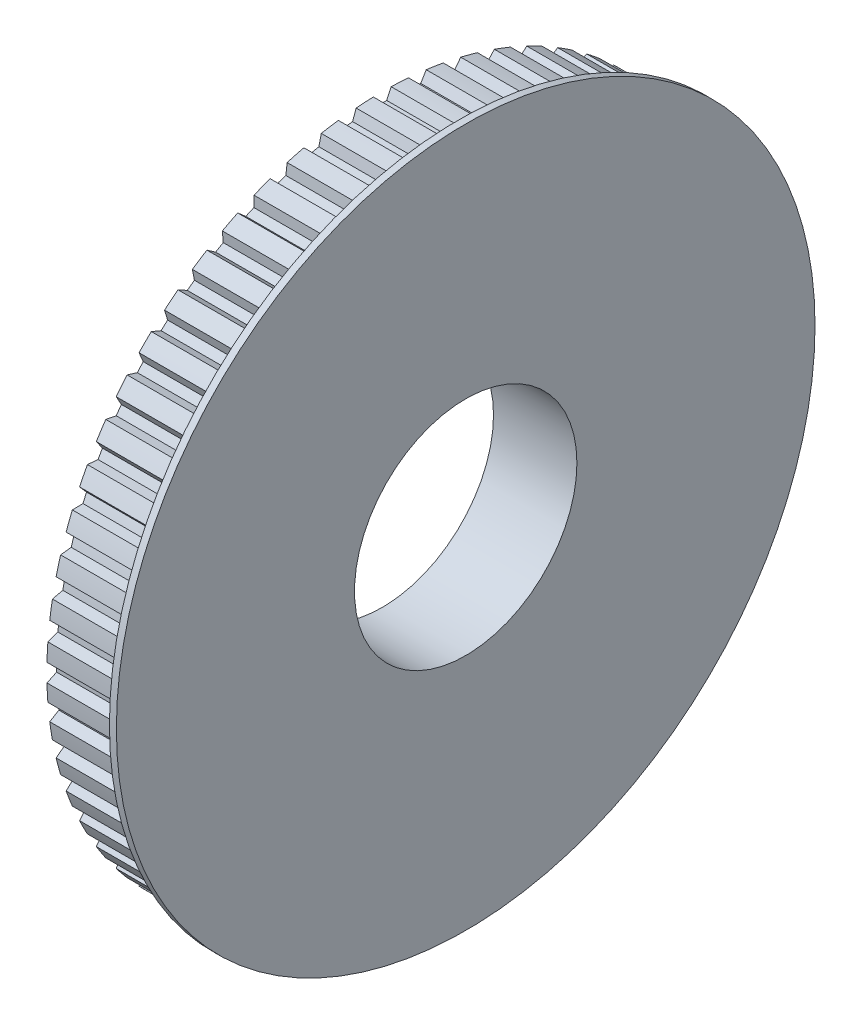
SolidWorks part; units mm, degrees
ref_plane "Front Plane" through (0, 0, 0) normal (0, 0, 1) x (1, 0, 0)
ref_plane "Top Plane" through (0, 0, 0) normal (0, 1, 0) x (1, 0, 0)
ref_plane "Right Plane" through (0, 0, 0) normal (1, 0, 0) x (0, 0, -1)
sketch "Sketch1" plane through (0, 0, 0) normal (1, 0, 0) x (0, 0, -1)
  line L0 (0, 48.255) -> (0, 0) construction
  circle A0 centre (0, 0) radius 48.255
  circle A1 centre (0, 0) radius 16
  point P19 (0, 0)
  dimension "D1" = 96.51
  dimension "D2" = 32
extrude "Boss-Extrude1" add sketch "Sketch1" along normal blind 11
sketch "Sketch2" plane through (0, 0, 0) normal (-1, 0, 0) x (0, 0, 1)
  line L0 (0, 0) -> (0, 48.255) construction
  line L1 (1.2819, 48.238) -> (0.635, 46.8507)
  line L2 (-1.2819, 48.238) -> (-0.635, 46.8507)
  line L3 (6.3171, 47.8397) -> (5.5287, 46.5277)
  line L4 (3.7674, 48.1077) -> (4.2657, 46.6604)
  line L5 (11.2831, 46.9173) -> (10.3619, 45.6949)
  line L6 (8.7754, 47.4504) -> (9.1197, 45.9589)
  line L7 (16.1255, 45.4809) -> (15.0816, 44.3614)
  line L8 (13.6872, 46.2732) -> (13.8738, 44.7539)
  line L9 (20.7912, 43.5462) -> (19.636, 42.542)
  line L10 (18.4491, 44.589) -> (18.4758, 43.0585)
  line L11 (25.2291, 41.1344) -> (23.9753, 40.2564)
  line L12 (23.0088, 42.4162) -> (22.8754, 40.8914)
  line L13 (29.3906, 38.2719) -> (28.0519, 37.5298)
  line L14 (27.3165, 39.7788) -> (27.0244, 38.2762)
  line L15 (33.2301, 34.9901) -> (31.8211, 34.392)
  line L16 (31.3249, 36.7055) -> (30.8774, 35.2417)
  line L17 (36.7055, 31.3249) -> (35.2417, 30.8774)
  line L18 (34.9901, 33.2301) -> (34.392, 31.8211)
  line L19 (39.7788, 27.3165) -> (38.2762, 27.0244)
  line L20 (38.2719, 29.3906) -> (37.5298, 28.0519)
  line L21 (42.4162, 23.0088) -> (40.8914, 22.8754)
  line L22 (41.1344, 25.2291) -> (40.2564, 23.9753)
  line L23 (44.589, 18.4491) -> (43.0585, 18.4758)
  line L24 (43.5462, 20.7912) -> (42.542, 19.636)
  line L25 (46.2732, 13.6872) -> (44.7539, 13.8738)
  line L26 (45.4809, 16.1255) -> (44.3614, 15.0816)
  line L27 (47.4504, 8.7754) -> (45.9589, 9.1197)
  line L28 (46.9173, 11.2831) -> (45.6949, 10.3619)
  line L29 (48.1077, 3.7674) -> (46.6604, 4.2657)
  line L30 (47.8397, 6.3171) -> (46.5277, 5.5287)
  line L31 (48.238, -1.2819) -> (46.8507, -0.635)
  line L32 (48.238, 1.2819) -> (46.8507, 0.635)
  line L33 (47.8397, -6.3171) -> (46.5277, -5.5287)
  line L34 (48.1077, -3.7674) -> (46.6604, -4.2657)
  line L35 (46.9173, -11.2831) -> (45.6949, -10.3619)
  line L36 (47.4504, -8.7754) -> (45.9589, -9.1197)
  line L37 (45.4809, -16.1255) -> (44.3614, -15.0816)
  line L38 (46.2732, -13.6872) -> (44.7539, -13.8738)
  line L39 (43.5462, -20.7912) -> (42.542, -19.636)
  line L40 (44.589, -18.4491) -> (43.0585, -18.4758)
  line L41 (41.1344, -25.2291) -> (40.2564, -23.9753)
  line L42 (42.4162, -23.0088) -> (40.8914, -22.8754)
  line L43 (38.2719, -29.3906) -> (37.5298, -28.0519)
  line L44 (39.7788, -27.3165) -> (38.2762, -27.0244)
  line L45 (34.9901, -33.2301) -> (34.392, -31.8211)
  line L46 (36.7055, -31.3249) -> (35.2417, -30.8774)
  line L47 (31.3249, -36.7055) -> (30.8774, -35.2417)
  line L48 (33.2301, -34.9901) -> (31.8211, -34.392)
  line L49 (27.3165, -39.7788) -> (27.0244, -38.2762)
  line L50 (29.3906, -38.2719) -> (28.0519, -37.5298)
  line L51 (23.0088, -42.4162) -> (22.8754, -40.8914)
  line L52 (25.2291, -41.1344) -> (23.9753, -40.2564)
  line L53 (18.4491, -44.589) -> (18.4758, -43.0585)
  line L54 (20.7912, -43.5462) -> (19.636, -42.542)
  line L55 (13.6872, -46.2732) -> (13.8738, -44.7539)
  line L56 (16.1255, -45.4809) -> (15.0816, -44.3614)
  line L57 (8.7754, -47.4504) -> (9.1197, -45.9589)
  line L58 (11.2831, -46.9173) -> (10.3619, -45.6949)
  line L59 (3.7674, -48.1077) -> (4.2657, -46.6604)
  line L60 (6.3171, -47.8397) -> (5.5287, -46.5277)
  line L61 (-1.2819, -48.238) -> (-0.635, -46.8507)
  line L62 (1.2819, -48.238) -> (0.635, -46.8507)
  line L63 (-6.3171, -47.8397) -> (-5.5287, -46.5277)
  line L64 (-3.7674, -48.1077) -> (-4.2657, -46.6604)
  line L65 (-11.2831, -46.9173) -> (-10.3619, -45.6949)
  line L66 (-8.7754, -47.4504) -> (-9.1197, -45.9589)
  line L67 (-16.1255, -45.4809) -> (-15.0816, -44.3614)
  line L68 (-13.6872, -46.2732) -> (-13.8738, -44.7539)
  line L69 (-20.7912, -43.5462) -> (-19.636, -42.542)
  line L70 (-18.4491, -44.589) -> (-18.4758, -43.0585)
  line L71 (-25.2291, -41.1344) -> (-23.9753, -40.2564)
  line L72 (-23.0088, -42.4162) -> (-22.8754, -40.8914)
  line L73 (-29.3906, -38.2719) -> (-28.0519, -37.5298)
  line L74 (-27.3165, -39.7788) -> (-27.0244, -38.2762)
  line L75 (-33.2301, -34.9901) -> (-31.8211, -34.392)
  line L76 (-31.3249, -36.7055) -> (-30.8774, -35.2417)
  line L77 (-36.7055, -31.3249) -> (-35.2417, -30.8774)
  line L78 (-34.9901, -33.2301) -> (-34.392, -31.8211)
  line L79 (-39.7788, -27.3165) -> (-38.2762, -27.0244)
  line L80 (-38.2719, -29.3906) -> (-37.5298, -28.0519)
  line L81 (-42.4162, -23.0088) -> (-40.8914, -22.8754)
  line L82 (-41.1344, -25.2291) -> (-40.2564, -23.9753)
  line L83 (-44.589, -18.4491) -> (-43.0585, -18.4758)
  line L84 (-43.5462, -20.7912) -> (-42.542, -19.636)
  line L85 (-46.2732, -13.6872) -> (-44.7539, -13.8738)
  line L86 (-45.4809, -16.1255) -> (-44.3614, -15.0816)
  line L87 (-47.4504, -8.7754) -> (-45.9589, -9.1197)
  line L88 (-46.9173, -11.2831) -> (-45.6949, -10.3619)
  line L89 (-48.1077, -3.7674) -> (-46.6604, -4.2657)
  line L90 (-47.8397, -6.3171) -> (-46.5277, -5.5287)
  line L91 (-48.238, 1.2819) -> (-46.8507, 0.635)
  line L92 (-48.238, -1.2819) -> (-46.8507, -0.635)
  line L93 (-47.8397, 6.3171) -> (-46.5277, 5.5287)
  line L94 (-48.1077, 3.7674) -> (-46.6604, 4.2657)
  line L95 (-46.9173, 11.2831) -> (-45.6949, 10.3619)
  line L96 (-47.4504, 8.7754) -> (-45.9589, 9.1197)
  line L97 (-45.4809, 16.1255) -> (-44.3614, 15.0816)
  line L98 (-46.2732, 13.6872) -> (-44.7539, 13.8738)
  line L99 (-43.5462, 20.7912) -> (-42.542, 19.636)
  line L100 (-44.589, 18.4491) -> (-43.0585, 18.4758)
  line L101 (-41.1344, 25.2291) -> (-40.2564, 23.9753)
  line L102 (-42.4162, 23.0088) -> (-40.8914, 22.8754)
  line L103 (-38.2719, 29.3906) -> (-37.5298, 28.0519)
  line L104 (-39.7788, 27.3165) -> (-38.2762, 27.0244)
  line L105 (-34.9901, 33.2301) -> (-34.392, 31.8211)
  line L106 (-36.7055, 31.3249) -> (-35.2417, 30.8774)
  line L107 (-31.3249, 36.7055) -> (-30.8774, 35.2417)
  line L108 (-33.2301, 34.9901) -> (-31.8211, 34.392)
  line L109 (-27.3165, 39.7788) -> (-27.0244, 38.2762)
  line L110 (-29.3906, 38.2719) -> (-28.0519, 37.5298)
  line L111 (-23.0088, 42.4162) -> (-22.8754, 40.8914)
  line L112 (-25.2291, 41.1344) -> (-23.9753, 40.2564)
  line L113 (-18.4491, 44.589) -> (-18.4758, 43.0585)
  line L114 (-20.7912, 43.5462) -> (-19.636, 42.542)
  line L115 (-13.6872, 46.2732) -> (-13.8738, 44.7539)
  line L116 (-16.1255, 45.4809) -> (-15.0816, 44.3614)
  line L117 (-8.7754, 47.4504) -> (-9.1197, 45.9589)
  line L118 (-11.2831, 46.9173) -> (-10.3619, 45.6949)
  line L119 (-3.7674, 48.1077) -> (-4.2657, 46.6604)
  line L120 (-6.3171, 47.8397) -> (-5.5287, 46.5277)
  circle A0 centre (0, 0) radius 48.255 construction
  arc A1 (1.2819, 48.238) -> (-1.2819, 48.238) centre (0, 0) ccw
  arc A2 (0.635, 46.8507) -> (-0.635, 46.8507) centre (0, 0) ccw
  arc A3 (6.3171, 47.8397) -> (3.7674, 48.1077) centre (0, 0) ccw
  arc A4 (5.5287, 46.5277) -> (4.2657, 46.6604) centre (0, 0) ccw
  arc A5 (11.2831, 46.9173) -> (8.7754, 47.4504) centre (0, 0) ccw
  arc A6 (10.3619, 45.6949) -> (9.1197, 45.9589) centre (0, 0) ccw
  arc A7 (16.1255, 45.4809) -> (13.6872, 46.2732) centre (0, 0) ccw
  arc A8 (15.0816, 44.3614) -> (13.8738, 44.7539) centre (0, 0) ccw
  arc A9 (20.7912, 43.5462) -> (18.4491, 44.589) centre (0, 0) ccw
  arc A10 (19.636, 42.542) -> (18.4758, 43.0585) centre (0, 0) ccw
  arc A11 (25.2291, 41.1344) -> (23.0088, 42.4162) centre (0, 0) ccw
  arc A12 (23.9753, 40.2564) -> (22.8754, 40.8914) centre (0, 0) ccw
  arc A13 (29.3906, 38.2719) -> (27.3165, 39.7788) centre (0, 0) ccw
  arc A14 (28.0519, 37.5298) -> (27.0244, 38.2762) centre (0, 0) ccw
  arc A15 (33.2301, 34.9901) -> (31.3249, 36.7055) centre (0, 0) ccw
  arc A16 (31.8211, 34.392) -> (30.8774, 35.2417) centre (0, 0) ccw
  arc A17 (36.7055, 31.3249) -> (34.9901, 33.2301) centre (0, 0) ccw
  arc A18 (35.2417, 30.8774) -> (34.392, 31.8211) centre (0, 0) ccw
  arc A19 (39.7788, 27.3165) -> (38.2719, 29.3906) centre (0, 0) ccw
  arc A20 (38.2762, 27.0244) -> (37.5298, 28.0519) centre (0, 0) ccw
  arc A21 (42.4162, 23.0088) -> (41.1344, 25.2291) centre (0, 0) ccw
  arc A22 (40.8914, 22.8754) -> (40.2564, 23.9753) centre (0, 0) ccw
  arc A23 (44.589, 18.4491) -> (43.5462, 20.7912) centre (0, 0) ccw
  arc A24 (43.0585, 18.4758) -> (42.542, 19.636) centre (0, 0) ccw
  arc A25 (46.2732, 13.6872) -> (45.4809, 16.1255) centre (0, 0) ccw
  arc A26 (44.7539, 13.8738) -> (44.3614, 15.0816) centre (0, 0) ccw
  arc A27 (47.4504, 8.7754) -> (46.9173, 11.2831) centre (0, 0) ccw
  arc A28 (45.9589, 9.1197) -> (45.6949, 10.3619) centre (0, 0) ccw
  arc A29 (48.1077, 3.7674) -> (47.8397, 6.3171) centre (0, 0) ccw
  arc A30 (46.6604, 4.2657) -> (46.5277, 5.5287) centre (0, 0) ccw
  arc A31 (48.238, -1.2819) -> (48.238, 1.2819) centre (0, 0) ccw
  arc A32 (46.8507, -0.635) -> (46.8507, 0.635) centre (0, 0) ccw
  arc A33 (47.8397, -6.3171) -> (48.1077, -3.7674) centre (0, 0) ccw
  arc A34 (46.5277, -5.5287) -> (46.6604, -4.2657) centre (0, 0) ccw
  arc A35 (46.9173, -11.2831) -> (47.4504, -8.7754) centre (0, 0) ccw
  arc A36 (45.6949, -10.3619) -> (45.9589, -9.1197) centre (0, 0) ccw
  arc A37 (45.4809, -16.1255) -> (46.2732, -13.6872) centre (0, 0) ccw
  arc A38 (44.3614, -15.0816) -> (44.7539, -13.8738) centre (0, 0) ccw
  arc A39 (43.5462, -20.7912) -> (44.589, -18.4491) centre (0, 0) ccw
  arc A40 (42.542, -19.636) -> (43.0585, -18.4758) centre (0, 0) ccw
  arc A41 (41.1344, -25.2291) -> (42.4162, -23.0088) centre (0, 0) ccw
  arc A42 (40.2564, -23.9753) -> (40.8914, -22.8754) centre (0, 0) ccw
  arc A43 (38.2719, -29.3906) -> (39.7788, -27.3165) centre (0, 0) ccw
  arc A44 (37.5298, -28.0519) -> (38.2762, -27.0244) centre (0, 0) ccw
  arc A45 (34.9901, -33.2301) -> (36.7055, -31.3249) centre (0, 0) ccw
  arc A46 (34.392, -31.8211) -> (35.2417, -30.8774) centre (0, 0) ccw
  arc A47 (31.3249, -36.7055) -> (33.2301, -34.9901) centre (0, 0) ccw
  arc A48 (30.8774, -35.2417) -> (31.8211, -34.392) centre (0, 0) ccw
  arc A49 (27.3165, -39.7788) -> (29.3906, -38.2719) centre (0, 0) ccw
  arc A50 (27.0244, -38.2762) -> (28.0519, -37.5298) centre (0, 0) ccw
  arc A51 (23.0088, -42.4162) -> (25.2291, -41.1344) centre (0, 0) ccw
  arc A52 (22.8754, -40.8914) -> (23.9753, -40.2564) centre (0, 0) ccw
  arc A53 (18.4491, -44.589) -> (20.7912, -43.5462) centre (0, 0) ccw
  arc A54 (18.4758, -43.0585) -> (19.636, -42.542) centre (0, 0) ccw
  arc A55 (13.6872, -46.2732) -> (16.1255, -45.4809) centre (0, 0) ccw
  arc A56 (13.8738, -44.7539) -> (15.0816, -44.3614) centre (0, 0) ccw
  arc A57 (8.7754, -47.4504) -> (11.2831, -46.9173) centre (0, 0) ccw
  arc A58 (9.1197, -45.9589) -> (10.3619, -45.6949) centre (0, 0) ccw
  arc A59 (3.7674, -48.1077) -> (6.3171, -47.8397) centre (0, 0) ccw
  arc A60 (4.2657, -46.6604) -> (5.5287, -46.5277) centre (0, 0) ccw
  arc A61 (-1.2819, -48.238) -> (1.2819, -48.238) centre (0, 0) ccw
  arc A62 (-0.635, -46.8507) -> (0.635, -46.8507) centre (0, 0) ccw
  arc A63 (-6.3171, -47.8397) -> (-3.7674, -48.1077) centre (0, 0) ccw
  arc A64 (-5.5287, -46.5277) -> (-4.2657, -46.6604) centre (0, 0) ccw
  arc A65 (-11.2831, -46.9173) -> (-8.7754, -47.4504) centre (0, 0) ccw
  arc A66 (-10.3619, -45.6949) -> (-9.1197, -45.9589) centre (0, 0) ccw
  arc A67 (-16.1255, -45.4809) -> (-13.6872, -46.2732) centre (0, 0) ccw
  arc A68 (-15.0816, -44.3614) -> (-13.8738, -44.7539) centre (0, 0) ccw
  arc A69 (-20.7912, -43.5462) -> (-18.4491, -44.589) centre (0, 0) ccw
  arc A70 (-19.636, -42.542) -> (-18.4758, -43.0585) centre (0, 0) ccw
  arc A71 (-25.2291, -41.1344) -> (-23.0088, -42.4162) centre (0, 0) ccw
  arc A72 (-23.9753, -40.2564) -> (-22.8754, -40.8914) centre (0, 0) ccw
  arc A73 (-29.3906, -38.2719) -> (-27.3165, -39.7788) centre (0, 0) ccw
  arc A74 (-28.0519, -37.5298) -> (-27.0244, -38.2762) centre (0, 0) ccw
  arc A75 (-33.2301, -34.9901) -> (-31.3249, -36.7055) centre (0, 0) ccw
  arc A76 (-31.8211, -34.392) -> (-30.8774, -35.2417) centre (0, 0) ccw
  arc A77 (-36.7055, -31.3249) -> (-34.9901, -33.2301) centre (0, 0) ccw
  arc A78 (-35.2417, -30.8774) -> (-34.392, -31.8211) centre (0, 0) ccw
  arc A79 (-39.7788, -27.3165) -> (-38.2719, -29.3906) centre (0, 0) ccw
  arc A80 (-38.2762, -27.0244) -> (-37.5298, -28.0519) centre (0, 0) ccw
  arc A81 (-42.4162, -23.0088) -> (-41.1344, -25.2291) centre (0, 0) ccw
  arc A82 (-40.8914, -22.8754) -> (-40.2564, -23.9753) centre (0, 0) ccw
  arc A83 (-44.589, -18.4491) -> (-43.5462, -20.7912) centre (0, 0) ccw
  arc A84 (-43.0585, -18.4758) -> (-42.542, -19.636) centre (0, 0) ccw
  arc A85 (-46.2732, -13.6872) -> (-45.4809, -16.1255) centre (0, 0) ccw
  arc A86 (-44.7539, -13.8738) -> (-44.3614, -15.0816) centre (0, 0) ccw
  arc A87 (-47.4504, -8.7754) -> (-46.9173, -11.2831) centre (0, 0) ccw
  arc A88 (-45.9589, -9.1197) -> (-45.6949, -10.3619) centre (0, 0) ccw
  arc A89 (-48.1077, -3.7674) -> (-47.8397, -6.3171) centre (0, 0) ccw
  arc A90 (-46.6604, -4.2657) -> (-46.5277, -5.5287) centre (0, 0) ccw
  arc A91 (-48.238, 1.2819) -> (-48.238, -1.2819) centre (0, 0) ccw
  arc A92 (-46.8507, 0.635) -> (-46.8507, -0.635) centre (0, 0) ccw
  arc A93 (-47.8397, 6.3171) -> (-48.1077, 3.7674) centre (0, 0) ccw
  arc A94 (-46.5277, 5.5287) -> (-46.6604, 4.2657) centre (0, 0) ccw
  arc A95 (-46.9173, 11.2831) -> (-47.4504, 8.7754) centre (0, 0) ccw
  arc A96 (-45.6949, 10.3619) -> (-45.9589, 9.1197) centre (0, 0) ccw
  arc A97 (-45.4809, 16.1255) -> (-46.2732, 13.6872) centre (0, 0) ccw
  arc A98 (-44.3614, 15.0816) -> (-44.7539, 13.8738) centre (0, 0) ccw
  arc A99 (-43.5462, 20.7912) -> (-44.589, 18.4491) centre (0, 0) ccw
  arc A100 (-42.542, 19.636) -> (-43.0585, 18.4758) centre (0, 0) ccw
  arc A101 (-41.1344, 25.2291) -> (-42.4162, 23.0088) centre (0, 0) ccw
  arc A102 (-40.2564, 23.9753) -> (-40.8914, 22.8754) centre (0, 0) ccw
  arc A103 (-38.2719, 29.3906) -> (-39.7788, 27.3165) centre (0, 0) ccw
  arc A104 (-37.5298, 28.0519) -> (-38.2762, 27.0244) centre (0, 0) ccw
  arc A105 (-34.9901, 33.2301) -> (-36.7055, 31.3249) centre (0, 0) ccw
  arc A106 (-34.392, 31.8211) -> (-35.2417, 30.8774) centre (0, 0) ccw
  arc A107 (-31.3249, 36.7055) -> (-33.2301, 34.9901) centre (0, 0) ccw
  arc A108 (-30.8774, 35.2417) -> (-31.8211, 34.392) centre (0, 0) ccw
  arc A109 (-27.3165, 39.7788) -> (-29.3906, 38.2719) centre (0, 0) ccw
  arc A110 (-27.0244, 38.2762) -> (-28.0519, 37.5298) centre (0, 0) ccw
  arc A111 (-23.0088, 42.4162) -> (-25.2291, 41.1344) centre (0, 0) ccw
  arc A112 (-22.8754, 40.8914) -> (-23.9753, 40.2564) centre (0, 0) ccw
  arc A113 (-18.4491, 44.589) -> (-20.7912, 43.5462) centre (0, 0) ccw
  arc A114 (-18.4758, 43.0585) -> (-19.636, 42.542) centre (0, 0) ccw
  arc A115 (-13.6872, 46.2732) -> (-16.1255, 45.4809) centre (0, 0) ccw
  arc A116 (-13.8738, 44.7539) -> (-15.0816, 44.3614) centre (0, 0) ccw
  arc A117 (-8.7754, 47.4504) -> (-11.2831, 46.9173) centre (0, 0) ccw
  arc A118 (-9.1197, 45.9589) -> (-10.3619, 45.6949) centre (0, 0) ccw
  arc A119 (-3.7674, 48.1077) -> (-6.3171, 47.8397) centre (0, 0) ccw
  arc A120 (-4.2657, 46.6604) -> (-5.5287, 46.5277) centre (0, 0) ccw
  point P10 (0, 46.855)
  point P18 (4.8977, 46.5983)
  point P23 (9.7417, 45.8311)
  point P28 (14.479, 44.5618)
  point P33 (19.0576, 42.8042)
  point P38 (23.4275, 40.5776)
  point P43 (27.5407, 37.9065)
  point P48 (31.3521, 34.8201)
  point P53 (34.8201, 31.3521)
  point P58 (37.9065, 27.5407)
  point P63 (40.5776, 23.4275)
  point P68 (42.8042, 19.0576)
  point P73 (44.5618, 14.479)
  point P78 (45.8311, 9.7417)
  point P83 (46.5983, 4.8977)
  point P88 (46.855, 0)
  point P93 (46.5983, -4.8977)
  point P98 (45.8311, -9.7417)
  point P103 (44.5618, -14.479)
  point P108 (42.8042, -19.0576)
  point P113 (40.5776, -23.4275)
  point P118 (37.9065, -27.5407)
  point P123 (34.8201, -31.3521)
  point P128 (31.3521, -34.8201)
  point P133 (27.5407, -37.9065)
  point P138 (23.4275, -40.5776)
  point P143 (19.0576, -42.8042)
  point P148 (14.479, -44.5618)
  point P153 (9.7417, -45.8311)
  point P158 (4.8977, -46.5983)
  point P159 (0, 0)
  point P161 (0, -46.855)
  point P166 (-4.8977, -46.5983)
  point P171 (-9.7417, -45.8311)
  point P176 (-14.479, -44.5618)
  point P181 (-19.0576, -42.8042)
  point P186 (-23.4275, -40.5776)
  point P191 (-27.5407, -37.9065)
  point P196 (-31.3521, -34.8201)
  point P201 (-34.8201, -31.3521)
  point P206 (-37.9065, -27.5407)
  point P211 (-40.5776, -23.4275)
  point P216 (-42.8042, -19.0576)
  point P221 (-44.5618, -14.479)
  point P226 (-45.8311, -9.7417)
  point P231 (-46.5983, -4.8977)
  point P236 (-46.855, 0)
  point P241 (-46.5983, 4.8977)
  point P246 (-45.8311, 9.7417)
  point P251 (-44.5618, 14.479)
  point P256 (-42.8042, 19.0576)
  point P261 (-40.5776, 23.4275)
  point P266 (-37.9065, 27.5407)
  point P271 (-34.8201, 31.3521)
  point P276 (-31.3521, 34.8201)
  point P281 (-27.5407, 37.9065)
  point P286 (-23.4275, 40.5776)
  point P291 (-19.0576, 42.8042)
  point P296 (-14.479, 44.5618)
  point P301 (-9.7417, 45.8311)
  point P306 (-4.8977, 46.5983)
  dimension "D1" = 1.4
  dimension "D2" = 25
  dimension "D3" = 0.635
  dimension "D4" = 60
extrude "Cut-Extrude1" cut sketch "Sketch2" against normal through all
sketch "Sketch4" plane through (11, 0, 0) normal (1, 0, 0) x (0, 0, -1)
  circle A0 centre (0, 0) radius 50.255
  circle A1 centre (0, 0) radius 16 construction
  circle A2 centre (0, 0) radius 16
  arc A3 (48.1077, -3.7674) -> (48.238, -1.2819) centre (0, 0) ccw construction
  dimension "D1" = 2
extrude "Boss-Extrude2" add sketch "Sketch4" along normal blind 1
